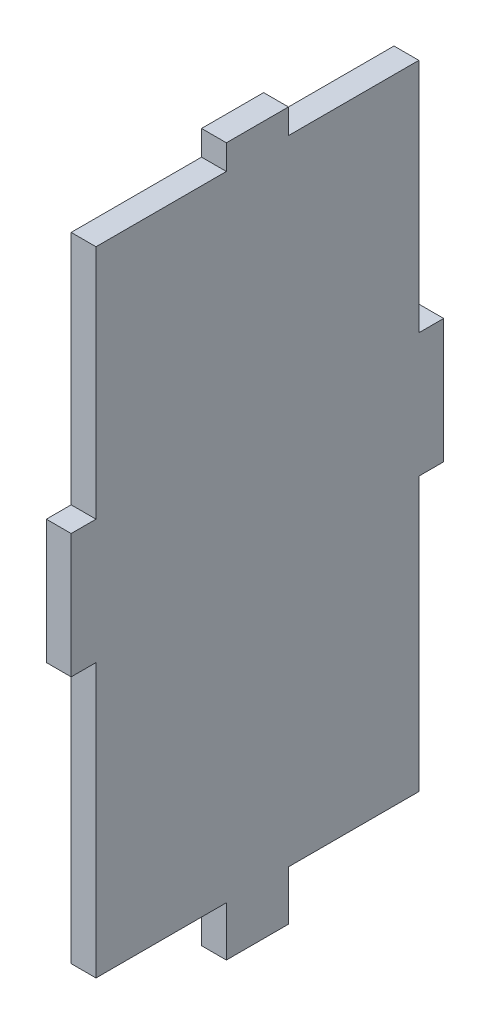
SolidWorks part; units mm, degrees
ref_plane "Front Plane" through (0, 0, 0) normal (0, 0, 1) x (1, 0, 0)
ref_plane "Top Plane" through (0, 0, 0) normal (0, 1, 0) x (1, 0, 0)
ref_plane "Right Plane" through (0, 0, 0) normal (1, 0, 0) x (0, 0, -1)
sketch "Sketch1" plane through (0, 0, 0) normal (1, 0, 0) x (0, 0, -1)
  line L0 (13, 0) -> (13, 51) construction
  line L1 (0, 0) -> (26, 0)
  line L2 (0, 0) -> (0, 51)
  line L3 (0, 51) -> (26, 51)
  line L4 (26, 0) -> (26, 51)
  line L5 (10.5, 51) -> (15.5, 51)
  line L6 (10.5, 51) -> (10.5, 53)
  line L7 (10.5, 53) -> (15.5, 53)
  line L8 (15.5, 51) -> (15.5, 53)
  line L9 (10.5, 0) -> (15.5, 0)
  line L10 (10.5, 0) -> (10.5, -4)
  line L11 (10.5, -4) -> (15.5, -4)
  line L12 (15.5, 0) -> (15.5, -4)
  line L13 (0, 32) -> (-2, 32)
  line L14 (0, 32) -> (0, 22)
  line L15 (0, 22) -> (-2, 22)
  line L16 (-2, 32) -> (-2, 22)
  line L17 (28, 32) -> (28, 22)
  line L18 (26, 22) -> (28, 22)
  line L19 (26, 32) -> (28, 32)
  point P17 (13, 51)
  point P18 (13, 53)
  point P19 (13, -4)
  point P20 (13, 0)
  dimension "D1" = 51
  dimension "D2" = 26
  dimension "D3" = 22
  dimension "D4" = 2
  dimension "D5" = 10
  dimension "D6" = 5
  dimension "D7" = 4
extrude "Boss-Extrude1" add sketch "Sketch1" along normal blind 2 contours L0 L9 L1 L4 L3 L5 | L1 L0 L3 L2 | L13 L16 L15 L2 | L19 L4 L18 L17 | L12 L9 L1 L10 L11
